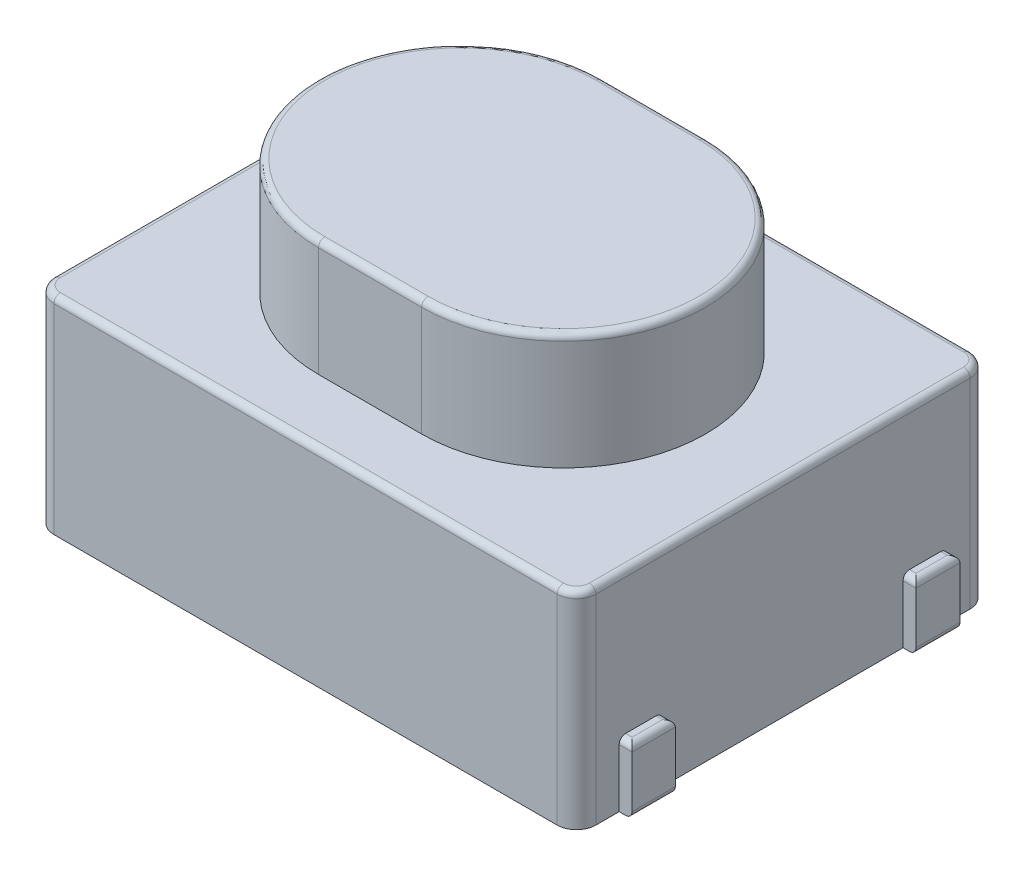
SolidWorks part; units mm, degrees
ref_plane "Plan de face" through (0, 0, 0) normal (0, 0, 1) x (1, 0, 0)
ref_plane "Plan de dessus" through (0, 0, 0) normal (0, 1, 0) x (1, 0, 0)
ref_plane "Plan de droite" through (0, 0, 0) normal (1, 0, 0) x (0, 0, -1)
sketch "Esquisse1" plane through (0, 0, 0) normal (0, 1, 0) x (1, 0, 0)
  line L1 (0.15, 0) -> (4.05, 0)
  line L2 (0, 0.15) -> (0, 3.05)
  line L3 (0.15, 3.2) -> (4.05, 3.2)
  line L4 (4.2, 0.15) -> (4.2, 3.05)
  arc A0 (0.15, 0) -> (0, 0.15) centre (0.15, 0.15) cw
  arc A1 (4.05, 0) -> (4.2, 0.15) centre (4.05, 0.15) ccw
  arc A2 (4.05, 3.2) -> (4.2, 3.05) centre (4.05, 3.05) cw
  arc A3 (0, 3.05) -> (0.15, 3.2) centre (0.15, 3.05) cw
  point P7 (0, 0)
  point P10 (4.2, 0)
  point P13 (4.2, 3.2)
  point P16 (0, 3.2)
  dimension "D3" = 0.15
  dimension "D1" = 4.2
  dimension "D2" = 3.2
extrude "Boss.-Extru.1" add sketch "Esquisse1" along normal blind 1.6
ref_plane "Plan1" through (0, 1.6, 0) normal (0, 1, 0) x (1, 0, 0)
sketch "Esquisse3" plane through (0, 1.6, 0) normal (0, 1, 0) x (1, 0, 0)
  line L0 (0, 1.6) -> (4.2, 1.6) construction
  line L1 (0, 3.05) -> (0, 0.15) construction
  line L2 (4.2, 0.15) -> (4.2, 3.05) construction
  line L3 (2.1, 3.2) -> (2.1, 0) construction
  line L4 (4.05, 3.2) -> (0.15, 3.2) construction
  line L5 (0.15, 0) -> (4.05, 0) construction
  line L6 (1.7, 1.6) -> (2.5, 1.6) construction
  line L7 (1.7, 2.7) -> (2.5, 2.7)
  line L8 (1.7, 0.5) -> (2.5, 0.5)
  arc A0 (1.7, 2.7) -> (1.7, 0.5) centre (1.7, 1.6) ccw
  arc A1 (2.5, 0.5) -> (2.5, 2.7) centre (2.5, 1.6) ccw
  point P14 (2.1, 1.6)
  point P19 (0.6, 1.6)
  point P20 (3.6, 1.6)
  dimension "D1" = 2.2
  dimension "D2" = 3
extrude "Boss.-Extru.2" add sketch "Esquisse3" along normal blind 0.9
fillet "Congé1" radius 0.05 4 edges at (2.1, 2.5, -2.7) (3.6, 2.5, -1.6) (2.1, 2.5, -0.5) (0.6, 2.5, -1.6)
sketch "Esquisse4" plane through (0, 0, 0) normal (0, 1, 0) x (1, 0, 0)
  line L0 (0, 2.7) -> (0, 2.872) construction
  line L1 (0, 3.05) -> (0, 0.15) construction
  line L2 (0, 2.7) -> (0, 2.5308) construction
  line L3 (4.2, 0.15) -> (4.2, 3.05) construction
  line L4 (0, 2.872) -> (-0.1, 2.872)
  line L5 (0, 2.872) -> (0, 2.5308)
  line L6 (0, 2.5308) -> (-0.1, 2.5308)
  line L7 (-0.1, 2.872) -> (-0.1, 2.5308)
  line L8 (4.2, 2.872) -> (4.3, 2.872)
  line L9 (4.2, 2.872) -> (4.2, 2.5308)
  line L10 (4.2, 2.5308) -> (4.3, 2.5308)
  line L11 (4.3, 2.872) -> (4.3, 2.5308)
  line L12 (0, 0.5) -> (0, 0.6658) construction
  line L13 (0, 0.5) -> (0, 0.3305) construction
  line L15 (0, 0.6658) -> (-0.1, 0.6658)
  line L16 (0, 0.6658) -> (0, 0.3305)
  line L17 (0, 0.3305) -> (-0.1, 0.3305)
  line L18 (-0.1, 0.6658) -> (-0.1, 0.3305)
  line L19 (4.2, 0.6658) -> (4.3, 0.6658)
  line L20 (4.2, 0.6658) -> (4.2, 0.3305)
  line L21 (4.2, 0.3305) -> (4.3, 0.3305)
  line L22 (4.3, 0.6658) -> (4.3, 0.3305)
  dimension "D1" = 0.1
  dimension "D2" = 0.1
  dimension "D3" = 0.1
  dimension "D4" = 0.1
extrude "Boss.-Extru.3" add sketch "Esquisse4" along normal blind 0.5
fillet "Congé2" radius 0.05 8 edges at (0.0439, 1.6, -0.0439) (0, 1.6, -1.6) (0.0439, 1.6, -3.1561) (2.1, 1.6, -3.2) (4.1561, 1.6, -3.1561) (4.2, 1.6, -1.6) (4.1561, 1.6, -0.0439) (2.1, 1.6, 0)
fillet "Congé3" radius 0.05 6 edges at (4.25, 0.5, -2.5308) (4.3, 0.5, -2.7014) (4.25, 0.5, -2.872) (4.25, 0.5, -0.6658) (4.25, 0.5, -0.3305) (4.3, 0.5, -0.4981)
fillet "Congé4" radius 0.05 6 edges at (-0.05, 0.5, -2.872) (-0.1, 0.5, -2.7014) (-0.05, 0.5, -2.5308) (-0.05, 0.5, -0.6658) (-0.1, 0.5, -0.4981) (-0.05, 0.5, -0.3305)
fillet "Congé5" radius 0.05 2 edges at (-0.1, 0, -2.7014) (-0.1, 0, -0.4981)
fillet "Congé6" radius 0.05 2 edges at (4.3, 0, -2.7014) (4.3, 0, -0.4981)
